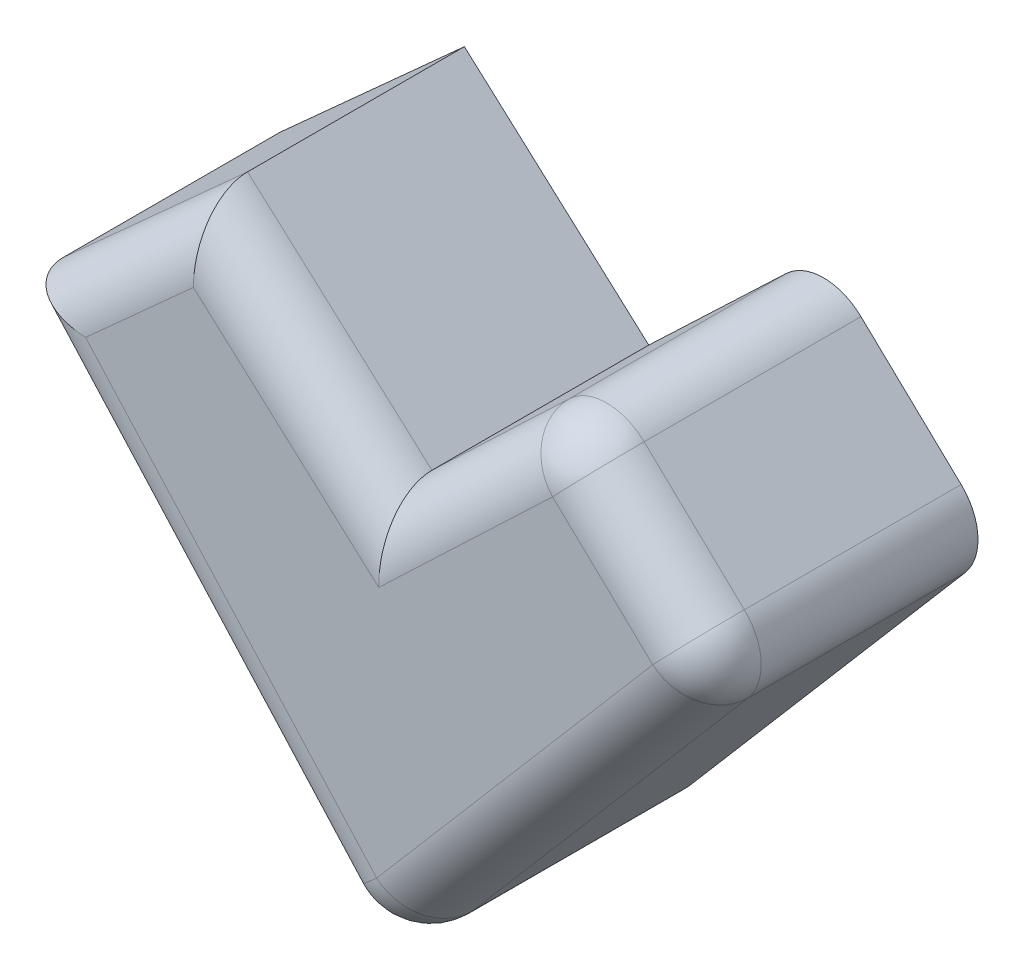
SolidWorks part; units mm, degrees
ref_plane "Front Plane" through (0, 0, 0) normal (0, 0, 1) x (1, 0, 0)
ref_plane "Top Plane" through (0, 0, 0) normal (0, 1, 0) x (1, 0, 0)
ref_plane "Right Plane" through (0, 0, 0) normal (1, 0, 0) x (0, 0, -1)
sketch "Sketch1" plane through (0, 0, 0) normal (0, 0, 1) x (1, 0, 0)
  line L0 (0, 0) -> (-68.0206, 75.4139)
  line L1 (-68.0206, 75.4139) -> (-34.0103, 106.09)
  line L2 (-34.0103, 106.09) -> (0, 75.4139)
  line L3 (0, 75.4139) -> (32.2527, 106.09)
  line L4 (32.2527, 106.09) -> (64.5054, 75.4139)
  line L5 (64.5054, 75.4139) -> (0, 0)
  line L6 (-34.0103, 106.09) -> (-34.0103, -29.4246) construction
  line L7 (32.2527, 106.09) -> (32.2527, -39.0148) construction
  dimension "D1" = 75.4139
  dimension "D2" = 132.526
  dimension "D3" = 106.09
extrude "Boss-Extrude1" add sketch "Sketch1" along normal blind 50
fillet "Fillet1" radius 10 9 edges at (-34.0103, 37.7069, 50) (-51.0155, 90.7519, 50) (-17.0052, 90.7519, 50) (16.1263, 90.7519, 50) (48.379, 90.7519, 50) (32.2527, 37.7069, 50) (0, 0, 25) (64.5054, 75.4139, 25) (32.2527, 106.09, 25)
equation "\"top_height\"=106.09"
equation "\"D3@Sketch1\"=\"top_height\""
equation "\"width\"=132.526"
equation "\"D2@Sketch1\"=\"width\""
equation "\"bottom_height\"=75.4139"
equation "\"D1@Sketch1\"=\"bottom_height\""
equation "\"thick\"=50"
equation "\"D1@Boss-Extrude1\"=\"thick\""
